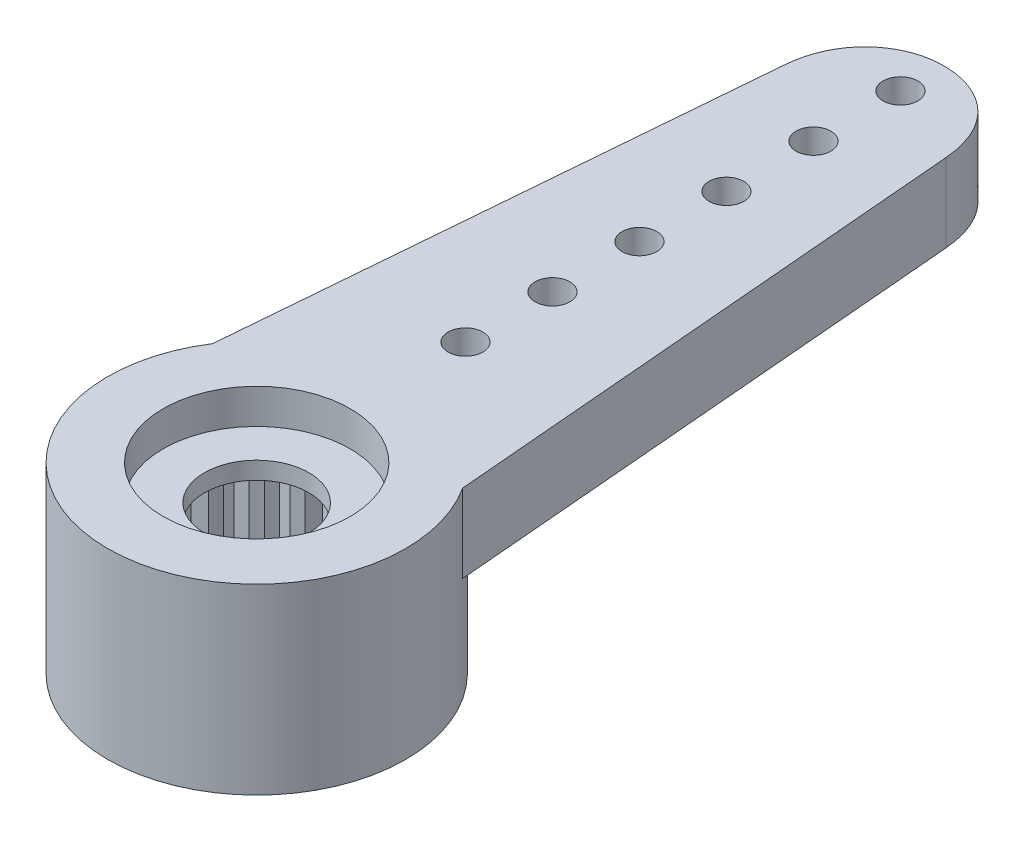
SolidWorks part; units mm, degrees
ref_plane "Front Plane" through (0, 0, 0) normal (0, 0, 1) x (1, 0, 0)
ref_plane "Top Plane" through (0, 0, 0) normal (0, 1, 0) x (1, 0, 0)
ref_plane "Right Plane" through (0, 0, 0) normal (1, 0, 0) x (0, 0, -1)
sketch "Sketch1" plane through (0, 0, 0) normal (0, 1, 0) x (1, 0, 0)
  circle A0 centre (0, 0) radius 3.425
  dimension "D1" = 6.85
extrude "HUB" add sketch "Sketch1" along normal blind 2.4
sketch "Sketch2" plane through (0, 2.4, 0) normal (0, 1, 0) x (1, 0, 0)
  line L0 (0, 0) -> (0, 16.2723) construction
  line L1 (-2.649, 14) -> (2.7333, 14) construction
  line L2 (-5.1175, 1.8615) -> (4.9374, 1.8615) construction
  line L3 (-2.875, 1.8615) -> (-1.85, 14)
  line L4 (2.875, 1.8615) -> (1.85, 14)
  line L5 (-1.7717, 14.9268) -> (-1.9284, 13.0721) construction
  line L6 (1.9338, 13.0078) -> (1.7662, 14.9922) construction
  line L7 (0.7058, 15.8) -> (-0.7062, 15.8) construction
  circle A0 centre (0, 0) radius 3.425 construction
  circle A1 centre (0, 14.8) radius 0.4
  circle A2 centre (0, 12.8) radius 0.4
  circle A3 centre (0, 10.8) radius 0.4
  circle A4 centre (0, 8.8) radius 0.4
  circle A5 centre (0, 6.8) radius 0.4
  circle A6 centre (0, 4.8) radius 0.4
  arc A7 (-2.875, 1.8615) -> (2.875, 1.8615) centre (0, 0) ccw
  spline S0 degree 3 poles (-1.85, 14) (-1.7619, 15.0433) (-0.8823, 15.8096) (0.8824, 15.8024) (1.7557, 15.1162) (1.85, 14) knots 0 0 0 0 0.45 0.55 1 1 1 1
  dimension "D4" = 0.8
  dimension "D1" = 14
  dimension "D2" = 3.7
  dimension "D3" = 5.75
  dimension "D5" = 1
  dimension "D6" = 6
extrude "Boss-Extrude2" add sketch "Sketch2" along normal blind 1.8
sketch "Sketch3" plane through (0, 4.2, 0) normal (0, 1, 0) x (1, 0, 0)
  circle A0 centre (0, 0) radius 2.15
  dimension "D1" = 4.3
extrude "Cut-Extrude1" cut sketch "Sketch3" against normal blind 0.8
sketch "Sketch4" plane through (0, 3.4, 0) normal (0, 1, 0) x (1, 0, 0)
  circle A0 centre (0, 0) radius 1.2
  dimension "D1" = 2.4
extrude "Cut-Extrude2" cut sketch "Sketch4" against normal through all
sketch "Sketch5" plane through (0, 0, 0) normal (0, -1, 0) x (1, 0, 0)
  line L0 (0, 0) -> (0, 4.9771) construction
  line L1 (0, 2.35) -> (-0.2103, 2.1397)
  line L2 (0, 2.35) -> (0.2103, 2.1397)
  circle A0 centre (0, 0) radius 2.15 construction
  arc A1 (-0.2103, 2.1397) -> (0.2103, 2.1397) centre (0, 0) cw
  point P7 (0, 2.15)
  dimension "D1" = 4.3
  dimension "D2" = 90
  dimension "D3" = 0.2
extrude "Cut-Extrude3" cut sketch "Sketch5" against normal blind 3 contours L1 A1 L2
pattern_circular "CirPattern1" count 20 over 360 about axis through (0, 0, 0) along (0, 1, 0) of "Cut-Extrude3"
sketch "Sketch6" plane through (0, 0, 0) normal (0, -1, 0) x (1, 0, 0)
  circle A0 centre (0, 0) radius 2.15
  arc A2 (0.2103, 2.1397) -> (-0.2103, 2.1397) centre (0, 0) ccw construction
extrude "Cut-Extrude4" cut sketch "Sketch6" against normal blind 3
